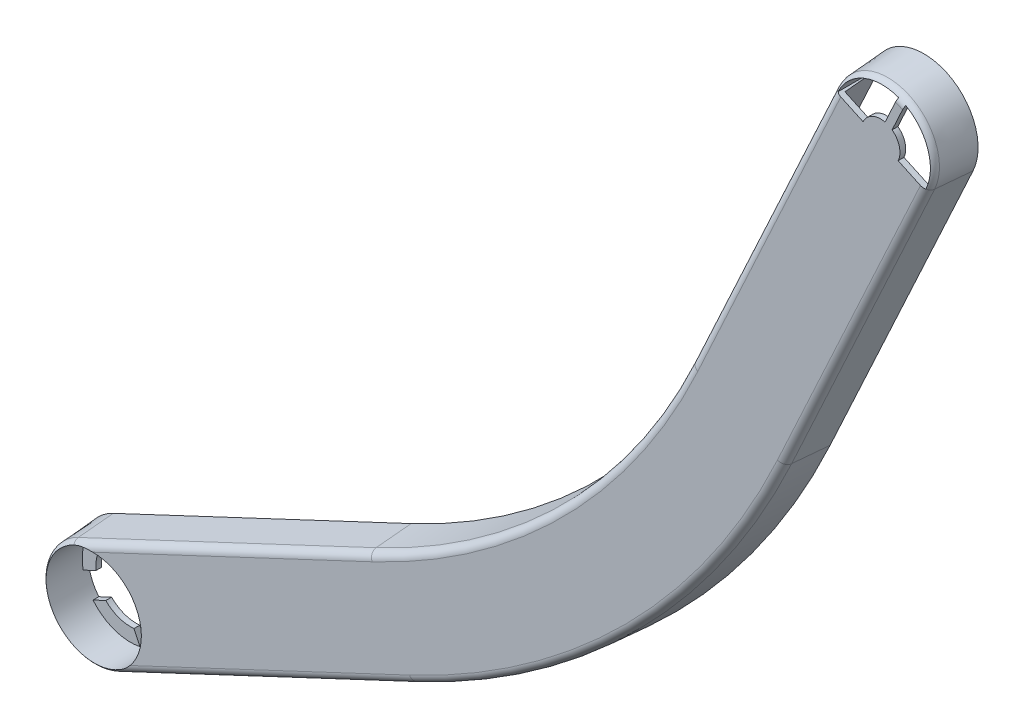
SolidWorks part; units mm, degrees
ref_plane "Plan de face" through (0, 0, 0) normal (0, 0, 1) x (1, 0, 0)
ref_plane "Plan de dessus" through (0, 0, 0) normal (0, 1, 0) x (1, 0, 0)
ref_plane "Plan de droite" through (0, 0, 0) normal (1, 0, 0) x (0, 0, -1)
ref_plane "Plan2" through (0, 0, -6.5) normal (0, 0, -1) x (-1, 0, 0)
sketch "Esquisse3" plane through (0, 0, -6.5) normal (0, 0, -1) x (-1, 0, 0)
  line L0 (-34.4181, 13.0524) -> (-71.3987, 93.0169)
  line L1 (125.5357, -106.6183) -> (48.5129, -70.405)
  line L2 (36.5994, -95.744) -> (113.6222, -131.9574)
  line L3 (-96.8126, 81.2639) -> (-59.832, 1.2994)
  arc A0 (-34.4181, 13.0524) -> (48.5129, -70.405) centre (121.696, 85.2493) ccw
  arc A1 (113.6222, -131.9574) -> (125.5357, -106.6183) centre (119.5789, -119.2878) ccw
  arc A2 (-59.832, 1.2994) -> (36.5994, -95.744) centre (121.696, 85.2493) ccw
  arc A3 (-71.3987, 93.0169) -> (-96.8126, 81.2639) centre (-84.1056, 87.1404) ccw
extrude "Extrusion2" add sketch "Esquisse3" against normal blind 11.2 draft 4
shell "Coque1" thickness 1.5
fillet "Congé1" radius 2 8 edges at (89.6534, 99.1365, 4.7) (53.6192, 52.7059, 4.7) (0.866, -36.5398, 4.7) (-86.6911, -89.2204, 4.7) (-131.5397, -124.9114, 4.7) (-75.444, -113.1419, 4.7) (19.6164, -55.172, 4.7) (77.6115, 41.6104, 4.7)
sketch "Esquisse4" plane through (0, 0, 4.7) normal (0, 0, 1) x (1, 0, 0)
  line L0 (84.1056, 87.1404) -> (93.7604, 108.0173) construction
  line L1 (34.4181, 13.0524) -> (71.3987, 93.0169) construction
  line L2 (88.428, 98.8692) -> (85.2543, 92.0066)
  line L3 (90.2433, 98.0297) -> (87.0696, 91.1671)
  line L4 (88.6438, 85.0416) -> (95.4511, 81.8935)
  line L5 (79.5674, 89.2391) -> (72.7601, 92.3872)
  circle A0 centre (-119.5789, -119.2878) radius 12.5
  arc A1 (95.4511, 81.8935) -> (90.2433, 98.0297) centre (84.1056, 87.1404) ccw
  arc A2 (88.6438, 85.0416) -> (87.0696, 91.1671) centre (84.1056, 87.1404) ccw
  arc A3 (85.2543, 92.0066) -> (79.5674, 89.2391) centre (84.1056, 87.1404) ccw
  arc A4 (88.428, 98.8692) -> (72.7601, 92.3872) centre (84.1056, 87.1404) ccw
  dimension "D1" = 25
  dimension "D2" = 25
  dimension "D3" = 10
  dimension "D4" = 1
  dimension "D5" = 2
extrude "Enlèv. mat.-Extru.1" cut sketch "Esquisse4" against normal through all
sketch "Esquisse5" plane through (0, 0, -6.5) normal (0, 0, -1) x (-1, 0, 0)
  line L0 (127.4569, -109.5828) -> (125.9042, -112.8854)
  line L1 (119.5789, -119.2878) -> (144.465, -130.9884) construction
  line L2 (125.5357, -106.6183) -> (48.5129, -70.405) construction
  line L3 (128.5343, -120.1833) -> (131.8368, -121.736)
  line L4 (125.9814, -125.6131) -> (129.284, -127.1658)
  line L5 (118.6835, -128.2432) -> (117.1307, -131.5457)
  arc A0 (118.6835, -128.2432) -> (125.9814, -125.6131) centre (119.5789, -119.2878) ccw
  arc A1 (117.1307, -131.5457) -> (129.284, -127.1658) centre (119.5789, -119.2878) ccw
  arc A2 (128.5343, -120.1833) -> (125.9042, -112.8854) centre (119.5789, -119.2878) ccw
  arc A3 (131.8368, -121.736) -> (127.4569, -109.5828) centre (119.5789, -119.2878) ccw
  dimension "D1" = 18
  dimension "D2" = 3
  dimension "D3" = 6
  dimension "D4" = 3
extrude "Extrusion3" add sketch "Esquisse5" against normal up to surface (1.5 mm away)
ref_plane "Plan3" through (-86.7464, -89.1026, 2.8395) normal (0.905, 0.4255, 0) x (0, 0, -1)
sketch "Esquisse6" plane through (-86.7464, -89.1026, 2.8395) normal (0.905, 0.4255, 0) x (0, 0, -1)
  line L0 (-1.8605, -13.3469) -> (17.4202, -13.3469) construction
  line L1 (-1.8605, -1.9951) -> (-1.8605, -24.6987) construction
  line L2 (-0.3605, -4.3469) -> (2.3395, -4.3469)
  line L3 (-0.3605, -25.165) -> (-0.3605, -1.5289) construction
  line L4 (-0.3605, -22.3469) -> (2.3395, -22.3469)
  line L5 (2.8395, -3.8469) -> (2.8395, -2.8469)
  line L6 (2.8395, -22.8469) -> (2.8395, -23.8469)
  line L7 (3.3395, -2.3469) -> (8.3395, -2.3469)
  line L8 (3.3395, -24.3469) -> (8.3395, -24.3469)
  line L9 (8.8395, -1.8469) -> (8.8395, -0.8855)
  line L10 (-0.3605, -1.5289) -> (9.3395, -0.8506) construction
  line L11 (8.8395, -24.8469) -> (8.8395, -25.8083)
  line L12 (9.3395, -1.2123) -> (9.3395, -4.8616) construction
  line L13 (8.8395, -0.8855) -> (-0.3605, -1.5289)
  line L14 (8.8395, -25.8083) -> (-0.3605, -25.165)
  line L15 (-0.3605, -1.5289) -> (-0.3605, -4.3469)
  line L16 (-0.3605, -25.165) -> (-0.3605, -22.3469)
  arc A0 (2.8395, -3.8469) -> (2.3395, -4.3469) centre (2.3395, -3.8469) cw
  arc A1 (2.8395, -2.8469) -> (3.3395, -2.3469) centre (3.3395, -2.8469) cw
  arc A2 (8.8395, -1.8469) -> (8.3395, -2.3469) centre (8.3395, -1.8469) cw
  arc A3 (2.8395, -22.8469) -> (2.3395, -22.3469) centre (2.3395, -22.8469) ccw
  arc A4 (3.3395, -24.3469) -> (2.8395, -23.8469) centre (3.3395, -23.8469) cw
  arc A5 (8.3395, -24.3469) -> (8.8395, -24.8469) centre (8.3395, -24.8469) cw
  point P25 (2.8395, -4.3469)
  point P28 (2.8395, -2.3469)
  point P31 (8.8395, -2.3469)
  point P34 (2.8395, -22.3469)
  point P37 (2.8395, -24.3469)
  point P40 (8.8395, -24.3469)
  dimension "D5" = 0.5
  dimension "D1" = 0.5
  dimension "D2" = 6
  dimension "D3" = 18
  dimension "D4" = 22
extrude "Extrusion4" add sketch "Esquisse6" along normal blind 1
ref_plane "Plan4" through (52.9084, 53.0346, -6.5) normal (0.4197, 0.9076, 0) x (-0.9076, 0.4197, 0)
sketch "Esquisse7" plane through (52.9084, 53.0346, -6.5) normal (0.4197, 0.9076, 0) x (-0.9076, 0.4197, 0)
  line L0 (-14, 14.9305) -> (-14, -2.9655) construction
  line L1 (-23, 9.7) -> (-23, 7)
  line L2 (-25.818, 9.7) -> (20.4626, 9.7) construction
  line L3 (-5, 9.7) -> (-5, 7)
  line L4 (-23.5, 6.5) -> (-24.5, 6.5)
  line L5 (-4.5, 6.5) -> (-3.5, 6.5)
  line L6 (-25, 6) -> (-25, 1)
  line L7 (-3, 6) -> (-3, 1)
  line L8 (-25.5, 0.5) -> (-26.4614, 0.5)
  line L9 (-25.818, 9.7) -> (-26.4963, 0) construction
  line L10 (-2.5, 0.5) -> (-1.5386, 0.5)
  line L11 (-26.4614, 0.5) -> (-25.818, 9.7)
  line L12 (-1.5386, 0.5) -> (-2.182, 9.7)
  line L13 (-25.818, 9.7) -> (-23, 9.7)
  line L14 (-2.182, 9.7) -> (-5, 9.7)
  line L15 (-26.4963, 0) -> (19.943, 0) construction
  arc A0 (-23.5, 6.5) -> (-23, 7) centre (-23.5, 7) ccw
  arc A1 (-25, 6) -> (-24.5, 6.5) centre (-24.5, 6) cw
  arc A2 (-25.5, 0.5) -> (-25, 1) centre (-25.5, 1) ccw
  arc A3 (-4.5, 6.5) -> (-5, 7) centre (-4.5, 7) cw
  arc A4 (-3, 6) -> (-3.5, 6.5) centre (-3.5, 6) ccw
  arc A5 (-2.5, 0.5) -> (-3, 1) centre (-2.5, 1) cw
  point P24 (-23, 6.5)
  point P27 (-25, 6.5)
  point P30 (-25, 0.5)
  point P33 (-5, 6.5)
  point P36 (-3, 6.5)
  point P39 (-3, 0.5)
  dimension "D6" = 0.5
  dimension "D1" = 14
  dimension "D2" = 18
  dimension "D3" = 22
  dimension "D4" = 0.5
  dimension "D5" = 6
extrude "Extrusion5" add sketch "Esquisse7" along normal blind 1
